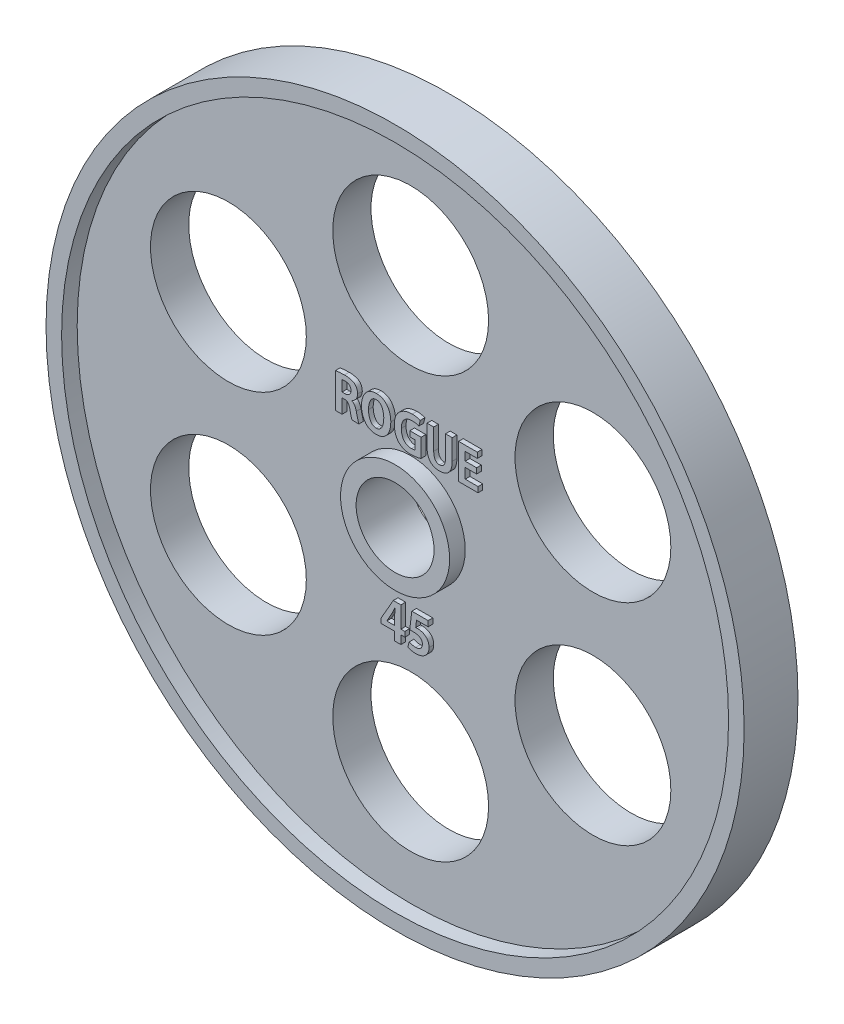
SolidWorks part; units mm, degrees
ref_plane "Front Plane" through (0, 0, 0) normal (0, 0, 1) x (1, 0, 0)
ref_plane "Top Plane" through (0, 0, 0) normal (0, 1, 0) x (1, 0, 0)
ref_plane "Right Plane" through (0, 0, 0) normal (1, 0, 0) x (0, 0, -1)
sketch "Sketch1" plane through (0, 0, 0) normal (0, 0, 1) x (1, 0, 0)
  circle A0 centre (0, 0) radius 224
  circle A1 centre (0, 0) radius 25
  dimension "D1" = 50
  dimension "D2" = 448
extrude "Boss-Extrude1" add sketch "Sketch1" along normal mid plane 34.544
sketch "Sketch2" plane through (0, 0, 17.272) normal (0, 0, 1) x (1, 0, 0)
  circle A0 centre (0, 0) radius 35
  circle A1 centre (0, 0) radius 214
  circle A2 centre (0, 0) radius 224 construction
  dimension "D1" = 10
  dimension "D2" = 35
extrude "Cut-Extrude1" cut sketch "Sketch2" against normal blind 10
sketch "Sketch3" plane through (0, 0, 7.272) normal (0, 0, 1) x (1, 0, 0)
  circle A0 centre (0, 135.0491) radius 50
  circle A1 centre (116.9559, 67.5245) radius 50
  circle A2 centre (116.9559, -67.5245) radius 50
  circle A3 centre (0, -135.0491) radius 50
  circle A4 centre (-116.9559, -67.5245) radius 50
  circle A5 centre (-116.9559, 67.5245) radius 50
  point P14 (0, 0)
  dimension "D1" = 100
  dimension "D2" = 6
extrude "Cut-Extrude2" cut sketch "Sketch3" against normal through all both and the other way through all
sketch "Sketch4" plane through (0, 0, 7.272) normal (0, 0, 1) x (1, 0, 0)
  text T0 "45" font "Adobe Gothic Std B" height in points 72
  text T1 "ROGUE" font "Adobe Gothic Std B" height in points 72
extrude "Boss-Extrude2" add sketch "Sketch4" along normal blind 3
